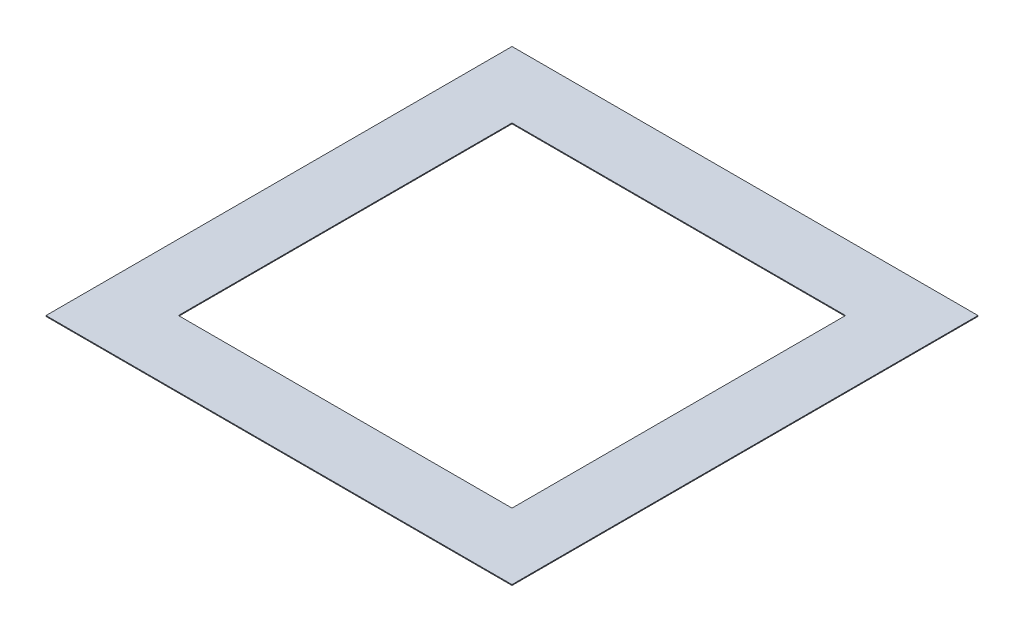
SolidWorks part; units mm, degrees
material "STYCAST 2850FT/Catalyst 23LV"
ref_plane "Front Plane" through (0, 0, 0) normal (0, 0, 1) x (1, 0, 0)
ref_plane "Top Plane" through (0, 0, 0) normal (0, 1, 0) x (1, 0, 0)
ref_plane "Right Plane" through (0, 0, 0) normal (1, 0, 0) x (0, 0, -1)
sketch "Sketch1" plane through (0, 0, 0) normal (0, 1, 0) x (1, 0, 0)
  line L1 (-69.85, -69.85) -> (69.85, -69.85)
  line L2 (-69.85, -69.85) -> (-69.85, 69.85)
  line L3 (-69.85, 69.85) -> (69.85, 69.85)
  line L4 (69.85, -69.85) -> (69.85, 69.85)
  line L5 (-69.85, -69.85) -> (69.85, 69.85) construction
  line L6 (-69.85, 69.85) -> (69.85, -69.85) construction
  line L7 (-50, -50) -> (50, -50)
  line L8 (-50, -50) -> (-50, 50)
  line L9 (-50, 50) -> (50, 50)
  line L10 (50, -50) -> (50, 50)
  line L11 (-50, -50) -> (50, 50) construction
  line L12 (-50, 50) -> (50, -50) construction
  point P0 (0, 0)
  point P6 (0, 0)
  dimension "D1" = 139.7
  dimension "D2" = 100
extrude "Boss-Extrude1" add sketch "Sketch1" along normal mid plane 0.25
equation "\"panel_width\"= 5.5in"
equation "\"finger_joint_width\"= 30mm"
equation "\"D1@Sketch1\"=\"panel_width\""
